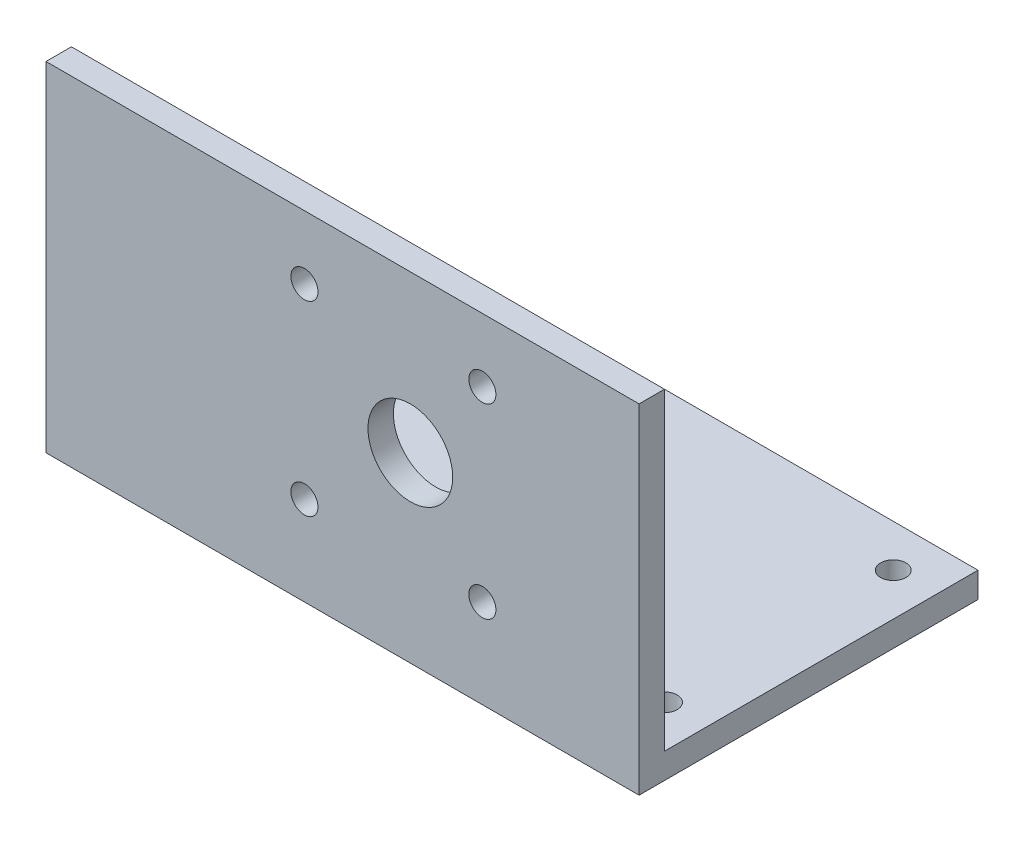
SolidWorks part; units mm, degrees
ref_plane "Спереди" through (0, 0, 0) normal (0, 0, 1) x (1, 0, 0)
ref_plane "Сверху" through (0, 0, 0) normal (0, 1, 0) x (1, 0, 0)
ref_plane "Справа" through (0, 0, 0) normal (1, 0, 0) x (0, 0, -1)
sketch "Эскиз1" plane through (0, 0, 0) normal (1, 0, 0) x (0, 0, -1)
  line L1 (-20, 20) -> (-17, 20)
  line L2 (-20, 20) -> (-20, -20)
  line L3 (-20, -20) -> (20, -20)
  line L4 (20, -17) -> (20, -20)
  line L5 (-20, 20) -> (20, -20) construction
  line L6 (-20, -20) -> (20, 20) construction
  line L7 (20, 20) -> (-17, 20) construction
  line L8 (20, 20) -> (20, -17) construction
  line L9 (20, -17) -> (-17, -17)
  line L10 (-17, 20) -> (-17, -17)
  point P0 (0, 0)
  dimension "D1" = 40
  dimension "D2" = 3
  dimension "D3" = 40
extrude "Бобышка-Вытянуть1" add sketch "Эскиз1" along normal blind 70
sketch "Эскиз2" plane through (0, 0, 20) normal (0, 0, 1) x (1, 0, 0)
  circle A0 centre (43, 1.5) radius 5
  arc A3 (40.7639, 3.5) -> (45.2361, 3.5) centre (43, 1.5) ccw construction
  circle A4 centre (51.5, 12.5) radius 1.6
  circle A5 centre (30.5, 12.5) radius 1.6
  circle A6 centre (30.5, -9.5) radius 1.6
  circle A7 centre (51.5, -9.5) radius 1.6
  circle A8 centre (51.5, 12.5) radius 1.5 construction
  circle A9 centre (30.5, 12.5) radius 1.5 construction
  circle A10 centre (30.5, -9.5) radius 1.5 construction
  circle A11 centre (51.5, -9.5) radius 1.5 construction
  dimension "D1" = 10
  dimension "D2" = 3.2
extrude "Вырез-Вытянуть1" cut sketch "Эскиз2" against normal up to surface (3 mm away) up to face at (35, 1.5, 17)
sketch "Эскиз3" plane through (0, -17, 0) normal (0, 1, 0) x (1, 0, 0)
  line L0 (70, 1.5) -> (0, 1.5) construction
  line L1 (70, 20) -> (70, -17) construction
  line L2 (0, 20) -> (0, -17) construction
  line L3 (65, 15) -> (65, 1.5) construction
  line L4 (65, 1.5) -> (65, -12) construction
  line L5 (35, 1.5) -> (35, -17) construction
  line L6 (70, -17) -> (0, -17) construction
  line L7 (70, 20) -> (0, 20) construction
  circle A0 centre (65, -12) radius 1.5
  circle A1 centre (65, 15) radius 1.5
  circle A2 centre (5, 15) radius 1.5
  circle A3 centre (5, -12) radius 1.5
  dimension "D1" = 3
  dimension "D2" = 5
  dimension "D3" = 5
  dimension "D4" = 27
  dimension "D5" = 60
extrude "Вырез-Вытянуть2" cut sketch "Эскиз3" against normal up to surface (3 mm away) up to face at (35, -20, 0)
